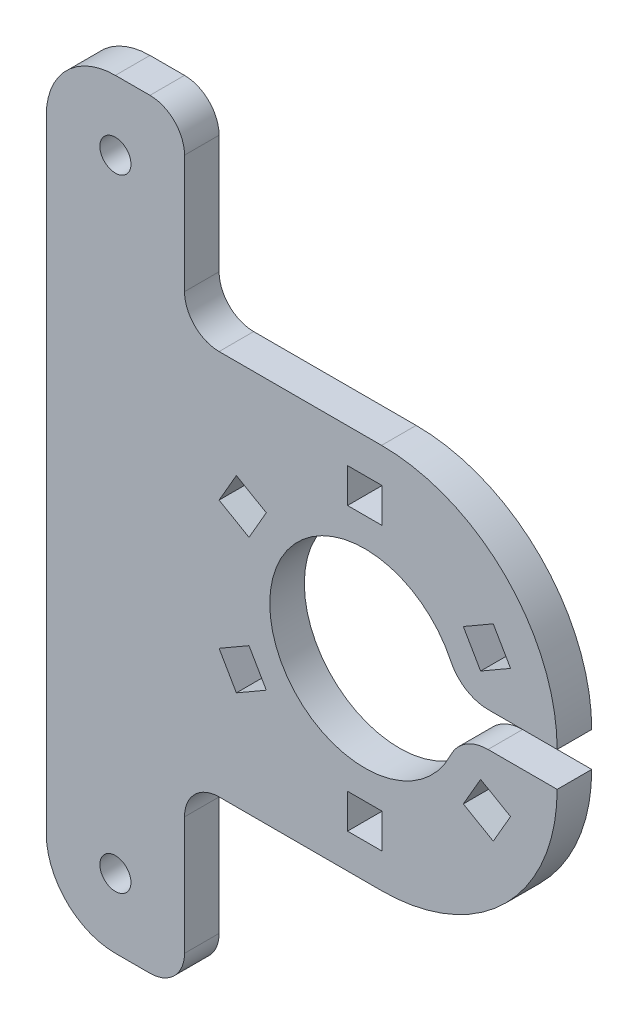
SolidWorks part; units mm, degrees
ref_plane "Plan de face" through (0, 0, 0) normal (0, 0, 1) x (1, 0, 0)
ref_plane "Plan de dessus" through (0, 0, 0) normal (0, 1, 0) x (1, 0, 0)
ref_plane "Plan de droite" through (0, 0, 0) normal (1, 0, 0) x (0, 0, -1)
sketch "Esquisse1" plane through (0, 0, 0) normal (0, 0, 1) x (1, 0, 0)
  line L0 (-58.9093, -55) -> (-63.9093, -55)
  line L1 (-73.9093, -45) -> (-73.9093, 45)
  line L2 (-63.9093, 55) -> (-58.9093, 55)
  line L3 (-53.9093, 50) -> (-53.9093, 32.9)
  line L4 (0, 2.5) -> (0, -2.5) construction
  line L5 (-48.9093, 27.9) -> (-25.4, 27.9)
  line L7 (-25.4, -27.9) -> (-48.9093, -27.9)
  line L8 (-53.9093, -32.9) -> (-53.9093, -50)
  line L17 (-60, 0) -> (0, 0) construction
  line L44 (-27.8273, 17.9) -> (-27.8273, 0) construction
  line L45 (-30.3273, 22.9) -> (-25.3273, 22.9)
  line L46 (-30.3273, 22.9) -> (-30.3273, 17.9)
  line L47 (-30.3273, 17.9) -> (-25.3273, 17.9)
  line L48 (-25.3273, 22.9) -> (-25.3273, 17.9)
  line L49 (-9.2453, 13.6151) -> (-6.7453, 9.2849)
  line L50 (-9.2453, 13.6151) -> (-13.5754, 11.1151)
  line L51 (-13.5754, 11.1151) -> (-11.0754, 6.7849)
  line L52 (-6.7453, 9.2849) -> (-11.0754, 6.7849)
  line L53 (-6.7453, -9.2849) -> (-9.2453, -13.6151)
  line L54 (-6.7453, -9.2849) -> (-11.0754, -6.7849)
  line L55 (-11.0754, -6.7849) -> (-13.5754, -11.1151)
  line L56 (-9.2453, -13.6151) -> (-13.5754, -11.1151)
  line L57 (-25.3273, -22.9) -> (-30.3273, -22.9)
  line L58 (-25.3273, -22.9) -> (-25.3273, -17.9)
  line L59 (-25.3273, -17.9) -> (-30.3273, -17.9)
  line L60 (-30.3273, -22.9) -> (-30.3273, -17.9)
  line L61 (-46.4093, -13.6151) -> (-48.9093, -9.2849)
  line L62 (-46.4093, -13.6151) -> (-42.0792, -11.1151)
  line L63 (-42.0792, -11.1151) -> (-44.5792, -6.7849)
  line L64 (-48.9093, -9.2849) -> (-44.5792, -6.7849)
  line L65 (-48.9093, 9.2849) -> (-46.4093, 13.6151)
  line L66 (-48.9093, 9.2849) -> (-44.5792, 6.7849)
  line L67 (-44.5792, 6.7849) -> (-42.0792, 11.1151)
  line L68 (-46.4093, 13.6151) -> (-42.0792, 11.1151)
  line L70 (0, 2.5) -> (-10, 2.5)
  line L71 (-10, -2.5) -> (0, -2.5)
  arc A0 (-25.4, 27.9) -> (0, 2.5) centre (-25.4, 2.5) cw
  arc A1 (-15.4159, 5.9177) -> (-15.4159, -5.9177) centre (-27.8273, 0) ccw
  arc A2 (-10, -2.5) -> (-15.4159, -5.9177) centre (-10, -8.5) ccw
  arc A3 (-10, 2.5) -> (-15.4159, 5.9177) centre (-10, 8.5) cw
  arc A4 (0, -2.5) -> (-25.4, -27.9) centre (-25.4, -2.5) cw
  arc A5 (-63.9093, -55) -> (-73.9093, -45) centre (-63.9093, -45) cw
  arc A6 (-73.9093, 45) -> (-63.9093, 55) centre (-63.9093, 45) cw
  arc A7 (-53.9093, -50) -> (-58.9093, -55) centre (-58.9093, -50) cw
  arc A8 (-53.9093, 50) -> (-58.9093, 55) centre (-58.9093, 50) ccw
  arc A9 (-48.9093, -27.9) -> (-53.9093, -32.9) centre (-48.9093, -32.9) ccw
  arc A10 (-53.9093, 32.9) -> (-48.9093, 27.9) centre (-48.9093, 32.9) ccw
  point P15 (-73.9093, 55)
  point P23 (-53.9093, -55)
  point P26 (-53.9093, 55)
  point P31 (-53.9093, 27.9)
  point P82 (-27.8273, 0)
  dimension "D10" = 27.5
  dimension "D17" = 6
  dimension "D5" = 10
  dimension "D8" = 5
  dimension "D2" = 20
  dimension "D3" = 5
  dimension "D4" = 10
  dimension "D6" = 5
  dimension "D7" = 110
  dimension "D11" = 17.9
  dimension "D12" = 5
  dimension "D13" = 6
  dimension "D15" = 5
extrude "Boss.-Extru.1" add sketch "Esquisse1" along normal blind 5
hole_wizard "Dégagement M41" positions "Esquisse2" profile "Esquisse3" hole size "M4" standard "ISO" end condition through all
sketch "Esquisse2" plane through (0, 0, 5) normal (0, 0, 1) x (1, 0, 0)
  point P0 (-63.9093, 45)
  point P2 (-63.9093, -45)
sketch "Esquisse3" plane through (-63.9093, 45, 5) normal (1, 0, 0) x (0, -1, 0)
  line L0 (0, 0) -> (0, 5)
  line L1 (0, 5) -> (2.25, 5)
  line L2 (2.25, 5) -> (2.25, 0)
  line L5 (2.25, 0) -> (0, 0)
  line L11 (0, -6.35) -> (0, 107.95) construction
  dimension "Diamètre du perçage jusqu'au prochain" = 4.5
  dimension "Profondeur du perçage jusqu'au prochain" = 5
